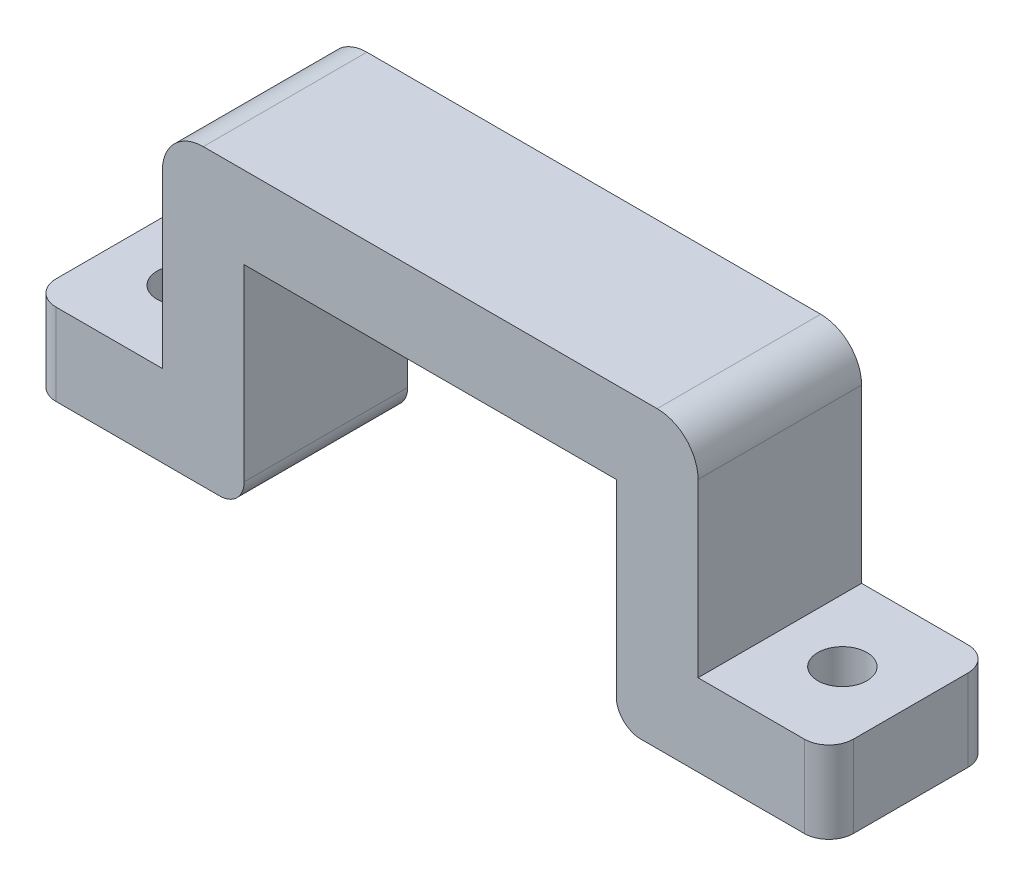
SolidWorks part; units mm, degrees
ref_plane "Plan de face" through (0, 0, 0) normal (0, 0, 1) x (1, 0, 0)
ref_plane "Plan de dessus" through (0, 0, 0) normal (0, 1, 0) x (1, 0, 0)
ref_plane "Plan de droite" through (0, 0, 0) normal (1, 0, 0) x (0, 0, -1)
sketch "Esquisse1" plane through (0, 0, 0) normal (0, 0, 1) x (1, 0, 0)
  line L0 (-16.375, 9) -> (-16.375, -6.5)
  line L1 (-11.375, 6.5) -> (11.375, 6.5)
  line L2 (-11.375, 6.5) -> (-11.375, -6.5)
  line L4 (11.375, 6.5) -> (11.375, -6.5)
  line L5 (-11.375, 6.5) -> (11.375, -6.5) construction
  line L6 (-11.375, -6.5) -> (11.375, 6.5) construction
  line L8 (16.375, 9) -> (16.375, -6.5)
  line L9 (-13.875, 11.5) -> (13.875, 11.5)
  line L10 (-16.375, -11.5) -> (16.375, -11.5) construction
  line L11 (-11.375, -6.5) -> (-16.375, -6.5)
  line L12 (-16.375, -6.5) -> (-11.375, -6.5)
  line L13 (11.375, -6.5) -> (16.375, -6.5)
  line L14 (-11.375, -6.5) -> (11.375, -6.5) construction
  line L15 (-16.375, 11.5) -> (-16.375, -11.5) construction
  line L16 (16.375, 11.5) -> (16.375, -11.5) construction
  line L17 (-16.375, 11.5) -> (16.375, 11.5) construction
  arc A0 (16.375, 9) -> (13.875, 11.5) centre (13.875, 9) ccw
  arc A1 (-16.375, 9) -> (-13.875, 11.5) centre (-13.875, 9) cw
  point P0 (0, 0)
  dimension "D4" = 2.5
  dimension "D1" = 22.75
  dimension "D2" = 13
  dimension "D3" = 5
extrude "Boss.-Extru.1" add sketch "Esquisse1" along normal blind 10 contours A1 L0 L11 L2 L1 L4 L13 L8 A0 L9
sketch "Esquisse2" plane through (-16.375, 0, 0) normal (-1, 0, 0) x (0, 0, 1)
  line L0 (10, 9) -> (10, -6.5) construction
  line L1 (0, -6.5) -> (10, -6.5)
  line L2 (0, -6.5) -> (0, -1.5)
  line L3 (0, -1.5) -> (10, -1.5)
  line L4 (10, -6.5) -> (10, -1.5)
  dimension "D1" = 5
extrude "Boss.-Extru.2" add sketch "Esquisse2" along normal blind 8
sketch "Esquisse3" plane through (16.375, 0, 0) normal (1, 0, 0) x (0, 0, -1)
  line L4 (0, -6.5) -> (0, -1.5)
  line L5 (-10, -6.5) -> (0, -6.5)
  line L6 (-10, -1.5) -> (-10, -6.5)
  line L7 (0, -1.5) -> (-10, -1.5)
  line L8 (0, -6.5) -> (0, -1.5)
  line L9 (-10, -6.5) -> (0, -6.5)
  line L10 (-10, -1.5) -> (-10, -6.5)
  line L11 (0, -1.5) -> (-10, -1.5)
  dimension "D1" = 0
extrude "Boss.-Extru.3" add sketch "Esquisse3" along normal blind 8
fillet "Congé1" radius 1.5 4 edges at (24.375, -4, 0) (24.375, -4, 10) (-24.375, -4, 0) (-24.375, -4, 10)
fillet "Congé2" radius 1.5 2 edges at (11.375, -6.5, 5) (-11.375, -6.5, 5)
sketch "Esquisse4" plane through (0, -1.5, 0) normal (0, 1, 0) x (1, 0, 0)
  line L0 (-22.875, -1.5) -> (-16.375, -10) construction
  line L1 (-22.875, -8.5) -> (-16.375, 0) construction
  line L2 (0, 0) -> (0, -10) construction
  line L3 (-13.875, -10) -> (13.875, -10) construction
  circle A0 centre (-20.1985, -5) radius 1.5
  circle A1 centre (20.1985, -5) radius 1.5
  dimension "D1" = 3
extrude "Enlèv. mat.-Extru.1" cut sketch "Esquisse4" against normal through all
